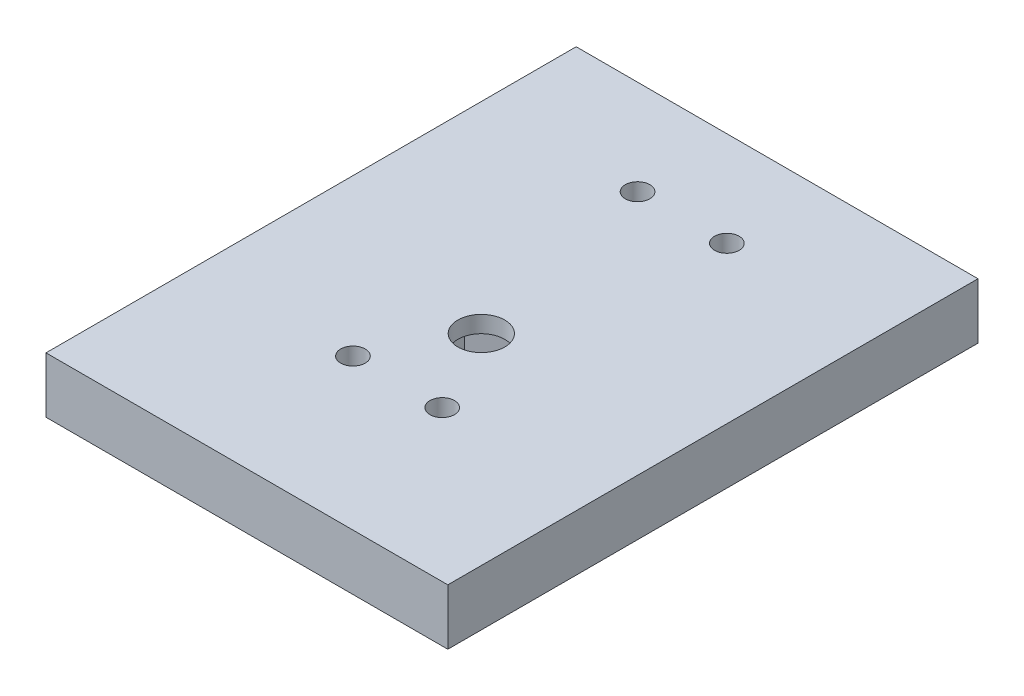
SolidWorks part; units mm, degrees
ref_plane "Front Plane" through (0, 0, 0) normal (0, 0, 1) x (1, 0, 0)
ref_plane "Top Plane" through (0, 0, 0) normal (0, 1, 0) x (1, 0, 0)
ref_plane "Right Plane" through (0, 0, 0) normal (1, 0, 0) x (0, 0, -1)
sketch "Sketch1" plane through (0, 0, 0) normal (0, 1, 0) x (1, 0, 0)
  line L0 (153.1607, 27.6724) -> (81.1607, 27.6724)
  line L1 (153.1607, 27.6724) -> (153.1607, -67.3276)
  line L2 (153.1607, -67.3276) -> (81.1607, -67.3276)
  line L3 (81.1607, 27.6724) -> (81.1607, -67.3276)
  circle A0 centre (125.1607, 10.6724) radius 2.2
  circle A1 centre (109.1607, 10.6724) radius 2.2
  circle A2 centre (125.1607, -40.3276) radius 2.1943
  circle A3 centre (109.1607, -40.3276) radius 2.2
extrude "Boss-Extrude1" add sketch "Sketch1" along normal blind 10
sketch "Sketch2" plane through (0, 0, 0) normal (0, -1, 0) x (1, 0, 0)
  line L2 (109.9607, 21.1706) -> (109.9607, 29.4845)
  line L3 (109.9607, 29.4845) -> (117.1607, 33.6414)
  line L4 (117.1607, 33.6414) -> (124.3607, 29.4845)
  line L5 (124.3607, 29.4845) -> (124.3607, 21.1706)
  line L6 (124.3607, 21.1706) -> (117.1607, 17.0137)
  line L7 (117.1607, 17.0137) -> (109.9607, 21.1706)
  point P19 (117.1607, 25.3276)
  dimension "D1" = 6
extrude "Cut-Extrude1" cut sketch "Sketch2" against normal blind 7
sketch "Sketch5" plane through (0, 7, 0) normal (0, -1, 0) x (1, 0, 0)
  line L0 (117.1607, 33.6414) -> (117.1607, 17.0137)
  circle A0 centre (117.1607, 25.3276) radius 4.2
extrude "Cut-Extrude2" cut sketch "Sketch5" against normal blind 7 contours L0 A0 | L0 A0
